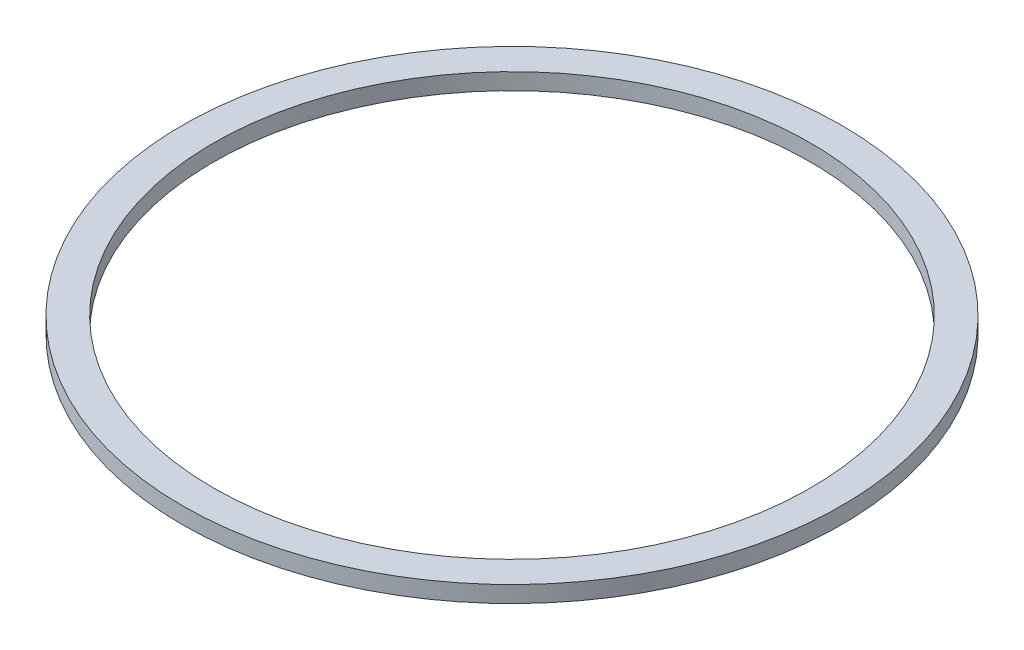
SolidWorks part; units mm, degrees
ref_plane "Front Plane" through (0, 0, 0) normal (0, 0, 1) x (1, 0, 0)
ref_plane "Top Plane" through (0, 0, 0) normal (0, 1, 0) x (1, 0, 0)
ref_plane "Right Plane" through (0, 0, 0) normal (1, 0, 0) x (0, 0, -1)
sketch "Sketch1" plane through (0, 0, 0) normal (0, 1, 0) x (1, 0, 0)
  circle A0 centre (0, 0) radius 72.5
  circle A1 centre (0, 0) radius 80
  dimension "D1" = 145
  dimension "D2" = 160
extrude "Boss-Extrude1" add sketch "Sketch1" along normal blind 4
